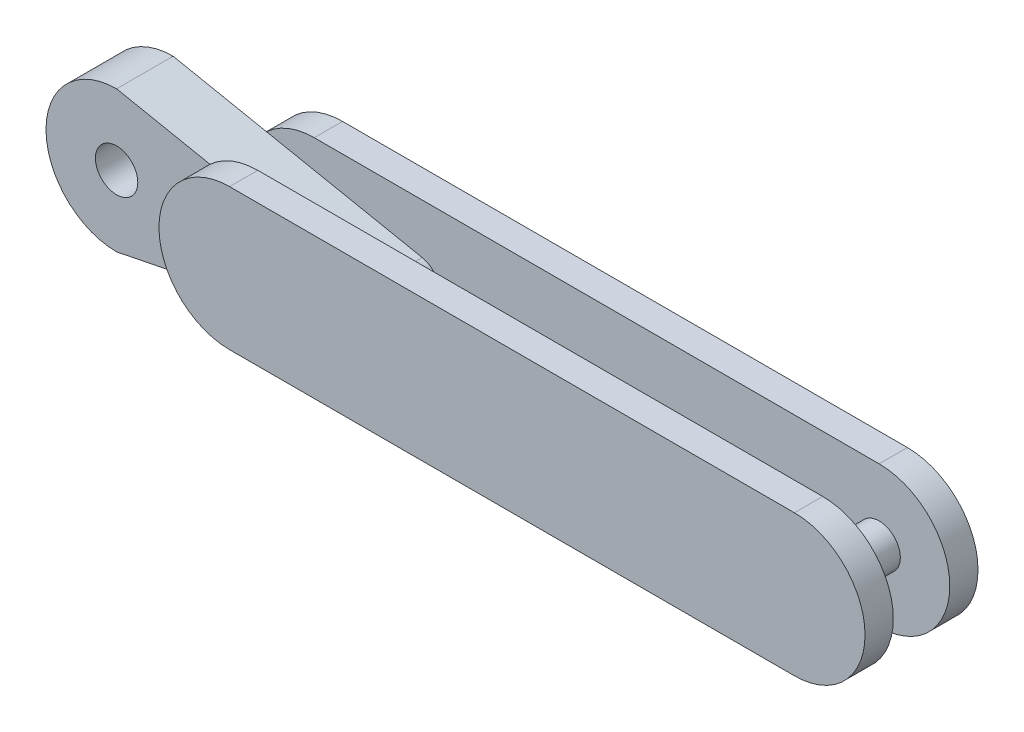
SolidWorks part; units mm, degrees
material "1060 Alloy"
ref_plane "Front Plane" through (0, 0, 0) normal (0, 0, 1) x (1, 0, 0)
ref_plane "Top Plane" through (0, 0, 0) normal (0, 1, 0) x (1, 0, 0)
ref_plane "Right Plane" through (0, 0, 0) normal (1, 0, 0) x (0, 0, -1)
sketch "Sketch4" plane through (0, 0, 0) normal (0, 0, 1) x (1, 0, 0)
  line L0 (-250, 0) -> (250, 0) construction
  line L1 (-250, 50) -> (250, 50)
  line L2 (-250, -50) -> (250, -50)
  arc A0 (-250, 50) -> (-250, -50) centre (-250, 0) ccw
  arc A1 (250, -50) -> (250, 50) centre (250, 0) ccw
  point P3 (0, 0)
  point P8 (110.1525, 0)
  point P9 (-250, 0)
  point P10 (0, 0)
  dimension "D2" = 50
  dimension "D1" = 500
extrude "Boss-Extrude2" add sketch "Sketch4" along normal mid plane 80
sketch "Sketch5" plane through (0, 0, 40) normal (0, 0, 1) x (1, 0, 0)
  line L0 (-150, 50) -> (-250, 50)
  line L1 (-250, -50) -> (-150, -50)
  arc A0 (-250, 50) -> (-250, -50) centre (-250, 0) ccw
  arc A2 (-150, 50) -> (-150, -50) centre (-150, 0) ccw
extrude "Cut-Extrude2" cut sketch "Sketch5" against normal blind 20
sketch "Sketch6" plane through (0, 0, -40) normal (0, 0, -1) x (-1, 0, 0)
  line L0 (150, 50) -> (250, 50)
  line L1 (150, -50) -> (250, -50)
  arc A0 (250, -50) -> (250, 50) centre (250, 0) ccw
  arc A2 (150, -50) -> (150, 50) centre (150, 0) ccw
extrude "Cut-Extrude3" cut sketch "Sketch6" against normal blind 20
sketch "Sketch9" plane through (0, 0, 20) normal (0, 0, 1) x (1, 0, 0)
  circle A0 centre (-250, 0) radius 15
extrude "Cut-Extrude5" cut sketch "Sketch9" against normal blind 40
ref_plane "Plane1" through (0, 0, 0) normal (0, 0, 1) x (1, 0, 0)
sketch "Sketch10" plane through (0, 0, 0) normal (0, 0, 1) x (1, 0, 0)
  line L12 (-250, 50) -> (-73.5436, 14.7087)
  line L14 (-250, 50) -> (250, 50)
  line L15 (250, -50) -> (-250, -50)
  line L17 (-73.5436, -14.7087) -> (-250, -50)
  arc A7 (250, -50) -> (250, 50) centre (250, 0) ccw
  arc A8 (-73.5436, -14.7087) -> (-73.5436, 14.7087) centre (-76.4853, 0) ccw
extrude "Cut-Extrude6" cut sketch "Sketch10" against normal mid plane 40
sketch "Sketch11" plane through (0, 0, 40) normal (0, 0, 1) x (1, 0, 0)
  circle A0 centre (250, 0) radius 15
sketch "Sketch13" plane through (0, 0, 40) normal (0, 0, 1) x (1, 0, 0)
  circle A0 centre (250, 0) radius 15
extrude "Boss-Extrude4" add sketch "Sketch13" against normal up to surface (60 mm away) up to face at (-31.9088, 0, -20)
extrude "Boss-Extrude3" add sketch "Sketch11" against normal blind 80
sketch "Sketch12" plane through (0, 0, 0) normal (0, 0, 1) x (1, 0, 0)
  point P0 (-250, 0)
  point P1 (0, 0)
  point P3 (0, 0)
  point P4 (0, 0)
move or copy body "Body-Move/Copy1" bodies to move or copy 110 copy no translate (250, 0, 0)
